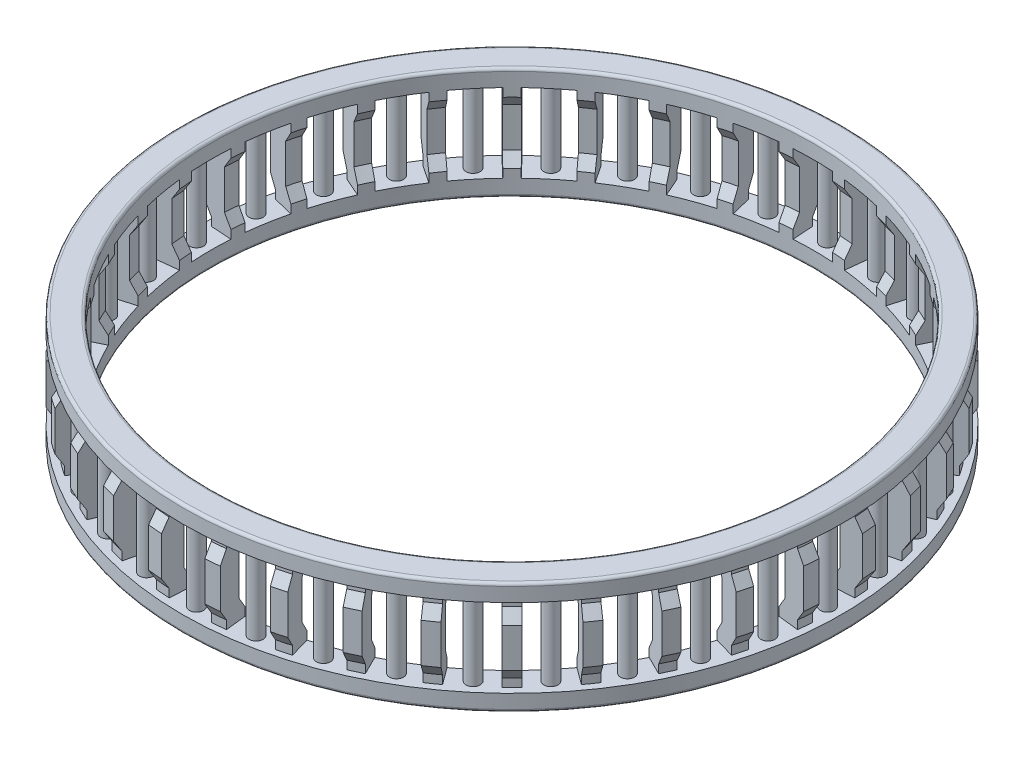
SolidWorks part; units mm, degrees
ref_plane "Front Plane" through (0, 0, 0) normal (0, 0, 1) x (1, 0, 0)
ref_plane "Top Plane" through (0, 0, 0) normal (0, 1, 0) x (1, 0, 0)
ref_plane "Right Plane" through (0, 0, 0) normal (1, 0, 0) x (0, 0, -1)
sketch "Sketch1" plane through (0, 0, 0) normal (0, 0, 1) x (1, 0, 0)
  line L0 (0, 12.5545) -> (0, 0) construction
  line L1 (0, 0) -> (-25.9559, 0) construction
  line L2 (-23.5, 2.6) -> (-23.5, 5.4)
  line L3 (-23.5, 5.4) -> (-23, 6.2)
  line L4 (-23, 6.2) -> (-23, 6.8)
  line L5 (-23, 6.8) -> (-23.5, 6.8)
  line L6 (-23.5, 6.8) -> (-23.5, 7.8)
  line L7 (-23.3, 8) -> (-21.7, 8)
  line L8 (-21.5, 7.8) -> (-21.5, 6.2)
  line L9 (-21.5, 6.2) -> (-22, 5.4)
  line L10 (-22, 5.4) -> (-22, 2.6)
  line L11 (-23.5, 4) -> (-22, 4) construction
  line L12 (-21.5, 1.8) -> (-22, 2.6)
  line L13 (-21.5, 0.2) -> (-21.5, 1.8)
  line L14 (-23.3, 0) -> (-21.7, 0)
  line L15 (-23.5, 1.2) -> (-23.5, 0.2)
  line L16 (-23, 1.2) -> (-23.5, 1.2)
  line L17 (-23, 1.8) -> (-23, 1.2)
  line L18 (-23.5, 2.6) -> (-23, 1.8)
  arc A0 (-21.5, 0.2) -> (-21.7, 0) centre (-21.7, 0.2) cw
  arc A1 (-23.3, 0) -> (-23.5, 0.2) centre (-23.3, 0.2) cw
  arc A2 (-21.7, 8) -> (-21.5, 7.8) centre (-21.7, 7.8) cw
  arc A3 (-23.5, 7.8) -> (-23.3, 8) centre (-23.3, 7.8) cw
  point P6 (0, 0)
  point P25 (-21.5, 0)
  point P28 (-23.5, 0)
  point P31 (-21.5, 8)
  point P34 (-23.5, 8)
  dimension "D8" = 0.2
  dimension "D1" = 23.5
  dimension "D2" = 2
  dimension "D3" = 1.2
  dimension "D4" = 1.4
  dimension "D5" = 0.6
  dimension "D6" = 4
  dimension "D7" = 1
revolve "Revolve1" add sketch "Sketch1" angle 360 about L0
sketch "Sketch2" plane through (0, 0, 0) normal (0, 1, 0) x (1, 0, 0)
  line L0 (0, 0) -> (-23.3, 0) construction
  line L1 (-23.6, 1.55) -> (-23.6, -1.55)
  line L2 (-21.3, 1.4) -> (-21.3, -1.4)
  line L3 (0, 0) -> (0, 3.829) construction
  line L4 (-23.6, 1.55) -> (-21.3, 1.4)
  line L5 (-21.3, -1.4) -> (-23.6, -1.55)
  line L6 (-21.5, 0) -> (-23.5, 0) construction
  circle A0 centre (0, 0) radius 23.3 construction
  circle A1 centre (0, 0) radius 21.5 construction
  circle A2 centre (0, 0) radius 23.5 construction
  circle A3 centre (-22.5, 0) radius 0.5
  point P10 (-23.6, 0)
  point P11 (-21.3, 0)
  dimension "D5" = 1
  dimension "D1" = 23.6
  dimension "D2" = 2.3
  dimension "D3" = 3.1
  dimension "D4" = 2.8
extrude "Cut-Extrude1" cut sketch "Sketch2" along normal up to surface (5.6 mm away) from offset 1.2 up to face at (0, 6.8, 23)
pattern_circular "CirPattern3" count 36 over 360 about axis through (0, 0, 0) along (0, 1, 0) of "Cut-Extrude1"
